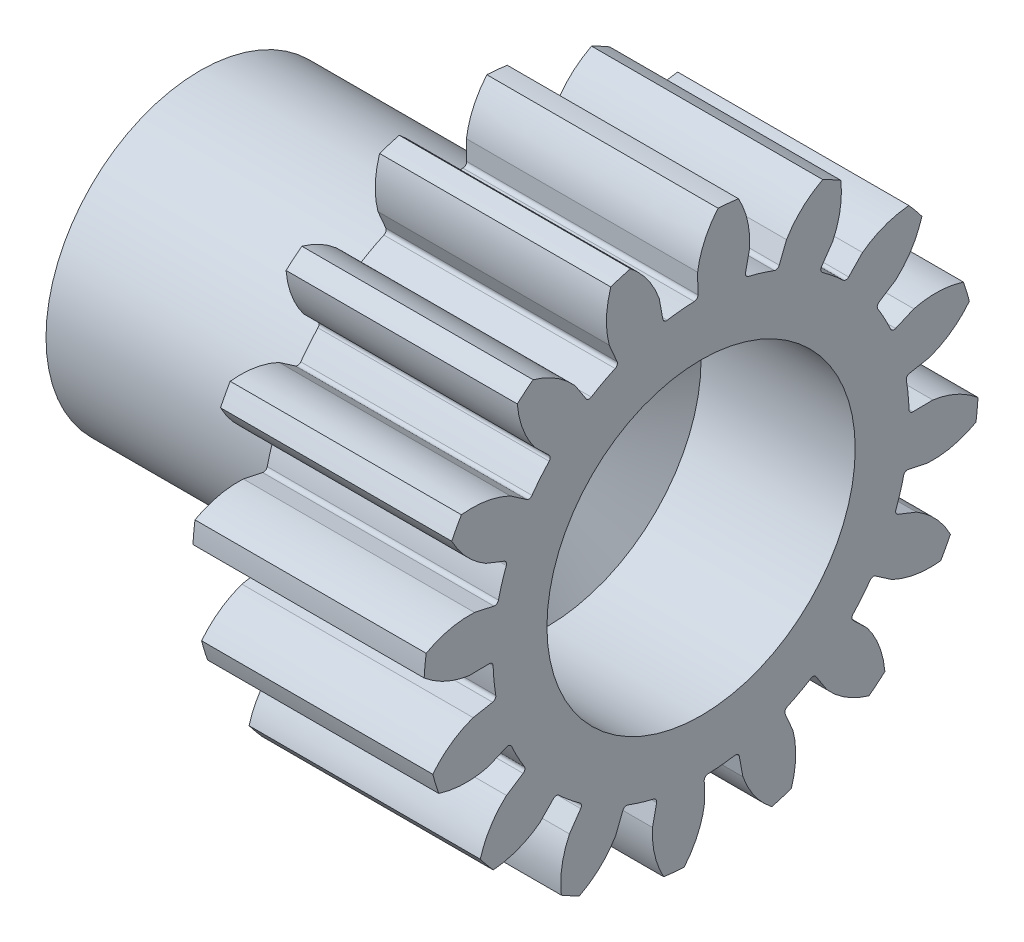
SolidWorks part; units mm, degrees
ref_plane "Спереди" through (0, 0, 0) normal (0, 0, 1) x (1, 0, 0)
ref_plane "Сверху" through (0, 0, 0) normal (0, 1, 0) x (1, 0, 0)
ref_plane "Справа" through (0, 0, 0) normal (1, 0, 0) x (0, 0, -1)
sketch "Эскиз2" plane through (0, 0, 0) normal (1, 0, 0) x (0, 0, -1)
  circle A0 centre (0, 0) radius 5.4
  dimension "D1" = 10.8
extrude "Бобышка-Вытянуть2" add sketch "Эскиз2" along normal blind 6
sketch "Эскиз5" plane through (0, 0, 0) normal (-1, 0, 0) x (0, 0, 1)
  circle A0 centre (0, 0) radius 4
  dimension "D1" = 8
extrude "Бобышка-Вытянуть4" add sketch "Эскиз5" along normal blind 7
hole_wizard "Отверстие обработанное метчиком M51" positions "Эскиз6" profile "Эскиз7" tap size "M5" standard "ISO"
sketch "Эскиз6" plane through (-7, 0, 0) normal (-1, 0, 0) x (0, 0, 1)
  point P0 (0, 0)
sketch "Эскиз7" plane through (-7, 0, 0) normal (0, 1, 0) x (0, 0, 1)
  line L0 (0, 0) -> (0, 15.2618)
  line L1 (0, 15.2618) -> (2.1, 14)
  line L2 (2.1, 14) -> (2.1, 0.925)
  line L3 (2.1, 0.925) -> (3.025, 0)
  line L5 (3.025, 0) -> (0, 0)
  line L6 (-2.1, 0.925) -> (-3.025, 0) construction
  line L10 (0, 15.2618) -> (-2.1, 14) construction
  line L11 (0, -6.35) -> (0, 107.95) construction
  dimension "Диаметр сверла" = 4.2
  dimension "Глубина сверла" = 14
  dimension "Диаметр передней зенковки" = 6.05
  dimension "Угол передней зенковки" = 90
  dimension "Угол заточки сверла" = 118
cosmetic thread "Отверстие резьбы1" parameters "D1"=9, "D2"=5
ref_plane "Плоскость2" through (3, 0, 0) normal (1, 0, 0) x (0, 0, -1)
sketch "Эскиз9" plane through (3, 0, 0) normal (1, 0, 0) x (0, 0, -1)
  line L0 (0, 0) -> (0, 6.4) construction
  line L1 (0, 6.4) -> (1.2306, 6.4) construction
  line L2 (0, 6.4) -> (2.0569, 5.6513) construction
  line L3 (0.4403, 7.1865) -> (3.6077, 4.8118) construction
  line L4 (0, 0) -> (-0.0896, 6.0134) construction
  line L5 (-0.0896, 6.0134) -> (-0.0805, 5.3994)
  line L6 (0, 0) -> (0.7057, 7.1653) construction
  line L7 (1.2611, 5.8803) -> (1.1323, 5.28)
  arc A0 (0.9702, 7.1343) -> (0.4403, 7.1865) centre (0, 0) ccw
  circle A1 centre (0, 0) radius 6.4 construction
  circle A2 centre (0, 0) radius 5.4 construction
  arc A3 (1.1323, 5.28) -> (-0.0805, 5.3994) centre (0, 0) ccw
  circle A4 centre (0, 0) radius 6.014 construction
  spline S0 degree 2 poles (-0.0896, 6.0134) (0.0048, 6.6659) (0.4403, 7.1865) knots 0 0 0 1 1 1
  spline S1 degree 2 poles (1.2611, 5.8803) (1.2957, 6.5388) (0.9702, 7.1343) knots 0 0 0 1 1 1
  point P11 (-0.0896, 6.0134)
  dimension "D1" = 12.8
  dimension "D2" = 14.4
  dimension "D3" = 20
  dimension "D4" = 2.1889
  dimension "D5" = 3.9587
  dimension "D8" = 5.625
  dimension "D6" = 1.7698
  dimension "D7" = 2.1889
extrude "Бобышка-Вытянуть5" add sketch "Эскиз9" along normal up to surface and the other way up to surface up to face at (6, 0, -2.1) other way up to face at (0, 0, 4)
fillet "Скругление4" radius 0.1 2 edges at (3, 5.3994, 0.0805) (3, 5.28, -1.1323)
pattern_circular "Круговой массив1" count 16 over 360 about axis through (6, 0, 0) along (-1, 0, 0) of "Бобышка-Вытянуть5", "Скругление4"
sketch "Эскиз11" plane through (0, 0, 0) normal (0, 0, 1) x (1, 0, 0)
  line L0 (0, 4) -> (0, 3.7)
  line L1 (0, 3.7) -> (-0.5, 3.7)
  line L2 (-0.5, 3.7) -> (-0.8, 4)
  line L3 (0, 4) -> (-7, 4) construction
  line L4 (-0.8, 4) -> (0, 4)
  dimension "D1" = 0.3
  dimension "D2" = 0.8
  dimension "D3" = 45
revolve "Вырез-Повернуть3" cut sketch "Эскиз11" angle 360 about axis through (-7, 0, 0) along (1, 0, 0)
fillet "Скругление5" radius 0.2 2 edges at (-0.5, 0, 3.7) (0, 0, 3.7)
hole_wizard "Диаметр отверстия Ø8.0 (8)1" positions "Эскиз13" profile "Эскиз15" hole size "Ø8.0" standard "ISO"
sketch "Эскиз13" plane through (6, 0, 0) normal (1, 0, 0) x (0, 0, -1)
  point P0 (0, 0)
sketch "Эскиз15" plane through (6, 0, 0) normal (0, 1, 0) x (0, 0, -1)
  line L0 (0, 0) -> (0, 6.4034)
  line L1 (0, 6.4034) -> (4, 4)
  line L2 (4, 4) -> (4, 0)
  line L5 (4, 0) -> (0, 0)
  line L10 (0, 6.4034) -> (-4, 4) construction
  line L11 (0, -6.35) -> (0, 107.95) construction
  dimension "Диаметр отверстия" = 8
  dimension "Глубина отверстия" = 4
  dimension "Угол заточки сверла" = 118
equation "\"Модуль\"= 0.8мм"
equation "\"Число2\"= 16"
equation "\"D1@Эскиз2\"= \"Модуль\" * (\"Число2\" - 2.5)"
equation "\"D1@Эскиз9\"= \"Модуль\" * \"Число2\""
equation "\"D2@Эскиз9\"= \"Модуль\" * (\"Число2\" + 2)"
equation "\"D6@Эскиз9\"= \"D5@Эскиз9\" - \"D4@Эскиз9\""
equation "\"D7@Эскиз9\"= \"D4@Эскиз9\""
equation "\"D8@Эскиз9\"= 90 / \"Число2\""
equation "\"D1@Круговой массив1\"= \"Число2\""
